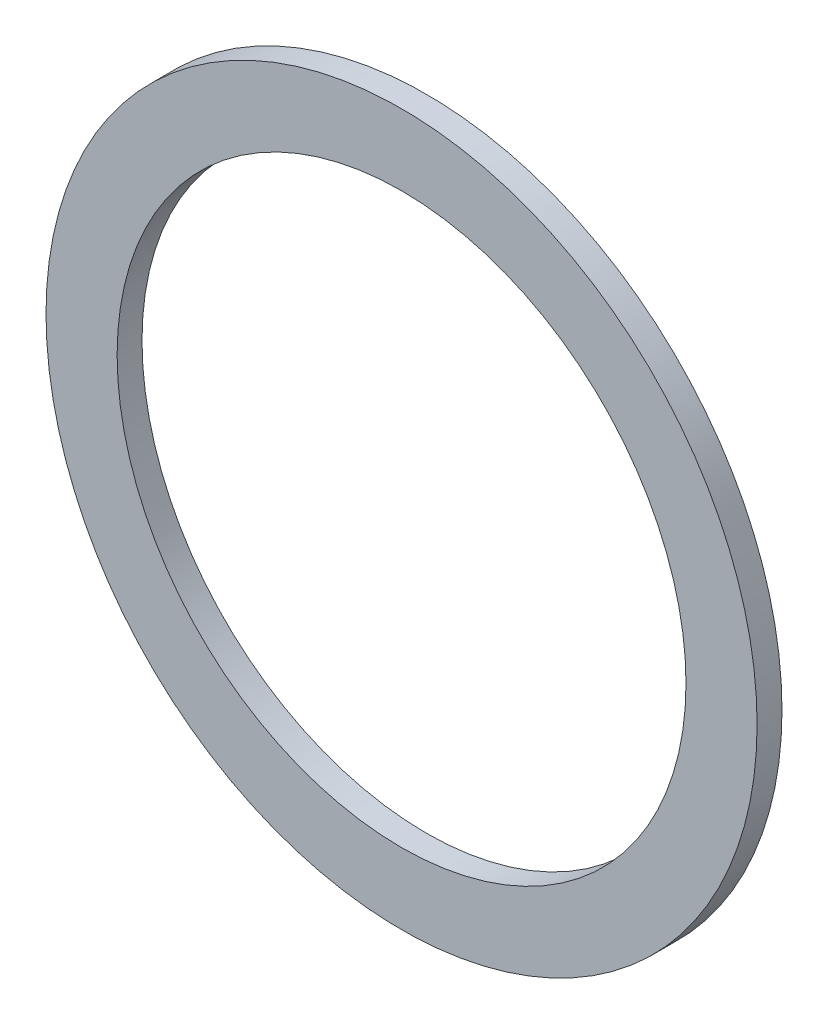
SolidWorks part; units mm, degrees
ref_plane "前视基准面" through (0, 0, 0) normal (0, 0, 1) x (1, 0, 0)
ref_plane "上视基准面" through (0, 0, 0) normal (0, 1, 0) x (1, 0, 0)
ref_plane "右视基准面" through (0, 0, 0) normal (1, 0, 0) x (0, 0, -1)
sketch "草图1" plane through (0, 0, 0) normal (0, 0, 1) x (1, 0, 0)
  circle A0 centre (0, 0) radius 80
  circle A1 centre (0, 0) radius 100
extrude "凸台-拉伸1" add sketch "草图1" along normal blind 7
